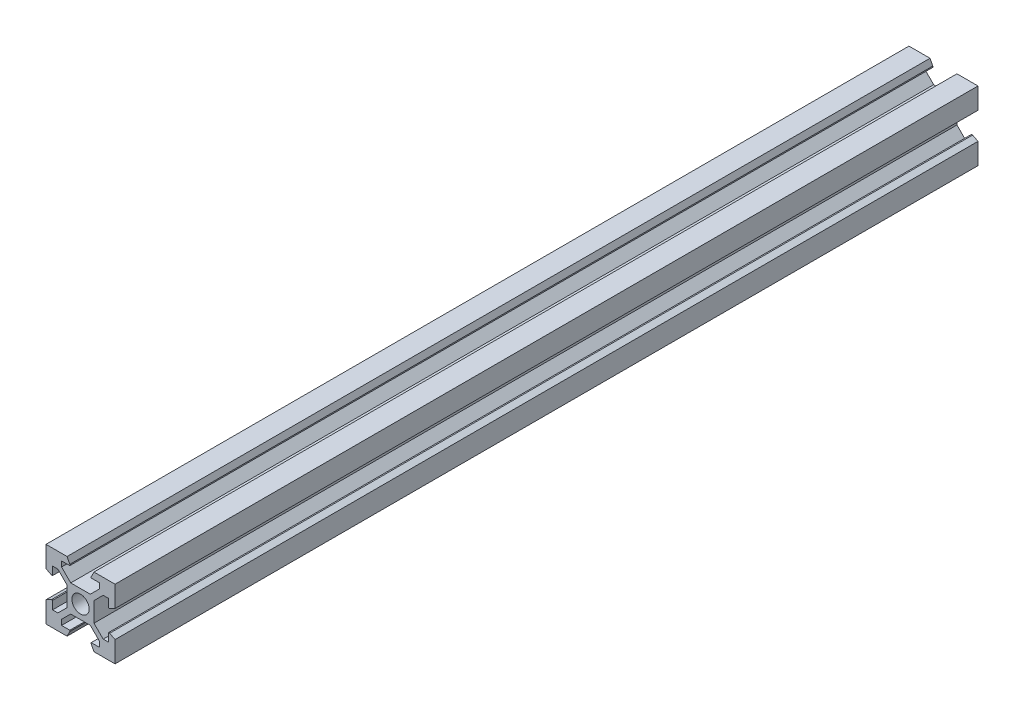
SolidWorks part; units mm, degrees
ref_plane "Front Plane" through (0, 0, 0) normal (0, 0, 1) x (1, 0, 0)
ref_plane "Top Plane" through (0, 0, 0) normal (0, 1, 0) x (1, 0, 0)
ref_plane "Right Plane" through (0, 0, 0) normal (1, 0, 0) x (0, 0, -1)
sketch "Sketch1" plane through (0, 0, 0) normal (0, 0, 1) x (1, 0, 0)
  line L0 (0, 20) -> (0, 13.8958)
  line L1 (0, 0) -> (20, 0)
  line L2 (0, 0) -> (0, 20)
  line L3 (0, 20) -> (20, 20)
  line L4 (20, 0) -> (20, 20)
  line L5 (0, 13.8958) -> (1.56, 13.1)
  line L6 (1.56, 13.1) -> (1.9, 13.1)
  line L7 (1.9, 13.1) -> (1.9, 15.5)
  line L8 (1.9, 15.5) -> (3.4393, 15.5)
  line L9 (3.4393, 15.5) -> (6.2656, 12.6737)
  line L10 (6.2656, 12.6737) -> (7.3263, 13.7344)
  line L11 (7.3263, 13.7344) -> (4.5, 16.5607)
  line L12 (4.5, 16.5607) -> (4.5, 18.1)
  line L13 (4.5, 18.1) -> (6.9, 18.1)
  line L14 (6.9, 18.1) -> (6.9, 18.44)
  line L15 (6.9, 18.44) -> (6.1, 20)
  line L16 (6.1, 20) -> (0, 20)
  line L17 (10, 10) -> (6.1, 13.9)
  line L18 (6.1, 6.1) -> (13.9, 6.1)
  line L19 (6.1, 6.1) -> (6.1, 13.9)
  line L20 (6.1, 13.9) -> (13.9, 13.9)
  line L21 (13.9, 6.1) -> (13.9, 13.9)
  line L22 (6.796, 13.204) -> (4.0494, 15.9506)
  line L23 (10, 10) -> (10, 24.9145) construction
  line L24 (13.1, 18.44) -> (13.9, 20)
  line L25 (13.1, 18.1) -> (13.1, 18.44)
  line L26 (15.5, 18.1) -> (13.1, 18.1)
  line L27 (15.5, 16.5607) -> (15.5, 18.1)
  line L28 (12.6737, 13.7344) -> (15.5, 16.5607)
  line L29 (13.7344, 12.6737) -> (12.6737, 13.7344)
  line L30 (16.5607, 15.5) -> (13.7344, 12.6737)
  line L31 (18.1, 15.5) -> (16.5607, 15.5)
  line L32 (18.1, 13.1) -> (18.1, 15.5)
  line L33 (18.44, 13.1) -> (18.1, 13.1)
  line L34 (20, 13.8958) -> (18.44, 13.1)
  line L35 (10, 10) -> (22.1718, 10)
  line L36 (20, 6.1042) -> (18.44, 6.9)
  line L37 (18.44, 6.9) -> (18.1, 6.9)
  line L38 (18.1, 6.9) -> (18.1, 4.5)
  line L39 (18.1, 4.5) -> (16.5607, 4.5)
  line L40 (16.5607, 4.5) -> (13.7344, 7.3263)
  line L41 (13.7344, 7.3263) -> (12.6737, 6.2656)
  line L42 (12.6737, 6.2656) -> (15.5, 3.4393)
  line L43 (15.5, 3.4393) -> (15.5, 1.9)
  line L44 (15.5, 1.9) -> (13.1, 1.9)
  line L45 (13.1, 1.9) -> (13.1, 1.56)
  line L46 (13.1, 1.56) -> (13.9, 0)
  line L47 (6.9, 1.56) -> (6.1, 0)
  line L48 (6.9, 1.9) -> (6.9, 1.56)
  line L49 (4.5, 1.9) -> (6.9, 1.9)
  line L50 (4.5, 3.4393) -> (4.5, 1.9)
  line L51 (7.3263, 6.2656) -> (4.5, 3.4393)
  line L52 (6.2656, 7.3263) -> (7.3263, 6.2656)
  line L53 (3.4393, 4.5) -> (6.2656, 7.3263)
  line L54 (1.9, 4.5) -> (3.4393, 4.5)
  line L55 (1.9, 6.9) -> (1.9, 4.5)
  line L56 (1.56, 6.9) -> (1.9, 6.9)
  line L57 (0, 6.1042) -> (1.56, 6.9)
  circle A0 centre (10, 10) radius 2.5
  point P21 (2.6697, 15.5)
  dimension "D3" = 5
  dimension "D1" = 20
  dimension "D2" = 20
  dimension "D4" = 10
  dimension "D5" = 10
  dimension "D6" = 7.8
  dimension "D7" = 7.8
  dimension "D8" = 6.1
  dimension "D9" = 6.1
  dimension "D10" = 6.9
  dimension "D11" = 6.9
  dimension "D12" = 6.1042
  dimension "D13" = 6.1
  dimension "D14" = 0.34
  dimension "D15" = 0.34
  dimension "D16" = 1.9
  dimension "D17" = 4.5
  dimension "D18" = 4.5
  dimension "D19" = 1.5
  dimension "D20" = 1.9
extrude "Boss-Extrude1" add sketch "Sketch1" along normal blind 250
